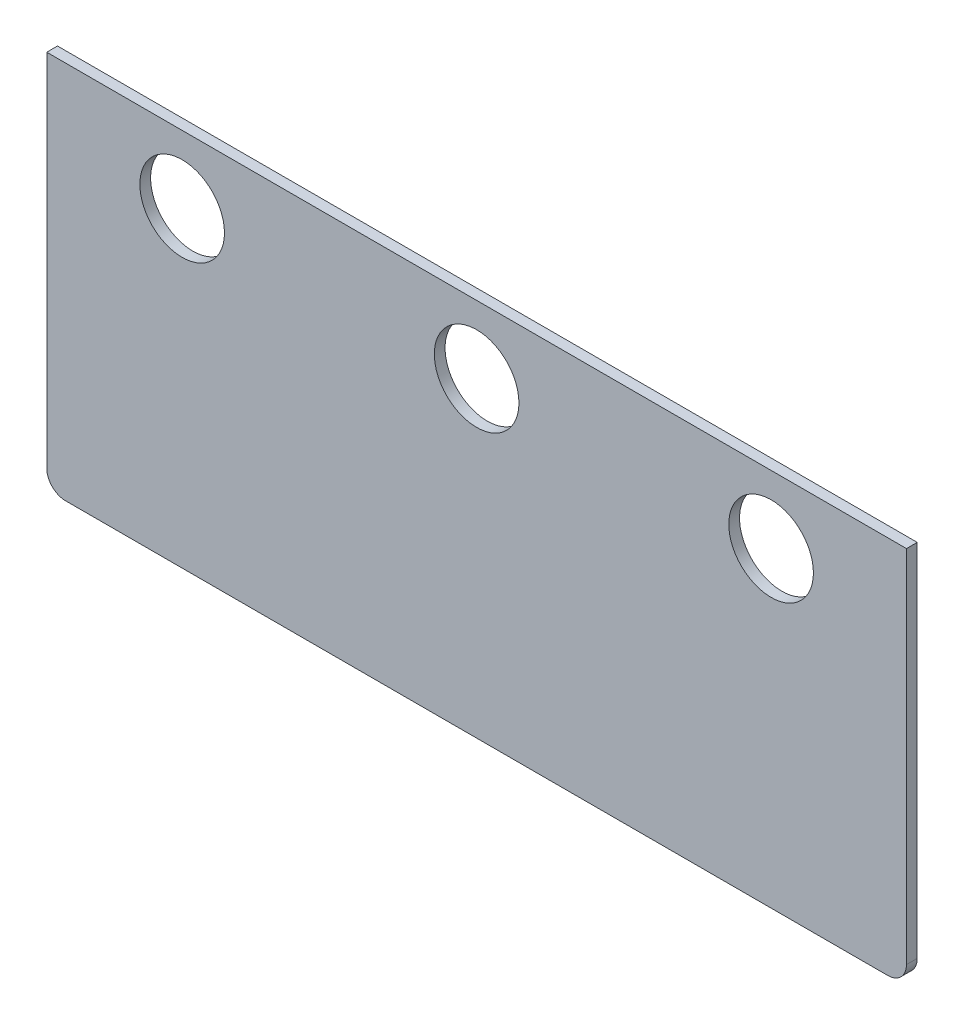
SolidWorks part; units mm, degrees
material "5052-H32"
ref_plane "Front Plane" through (0, 0, 0) normal (0, 0, 1) x (1, 0, 0)
ref_plane "Top Plane" through (0, 0, 0) normal (0, 1, 0) x (1, 0, 0)
ref_plane "Right Plane" through (0, 0, 0) normal (1, 0, 0) x (0, 0, -1)
sketch "Sketch1" plane through (0, 0, 0) normal (0, 0, 1) x (1, 0, 0)
  line L0 (-127, 112) -> (-127, 0)
  line L2 (127, 0) -> (127, 112)
  line L3 (127, 112) -> (-127, 112)
  line L4 (-127, 0) -> (127, 0)
  circle A0 centre (87, 92) radius 12.5
  circle A1 centre (0, 92) radius 12.5
  circle A2 centre (-87, 92) radius 12.5
  point P11 (0, 112)
  point P22 (0, 0)
  dimension "D4" = 25
  dimension "D1" = 112
  dimension "D2" = 254
  dimension "D3" = 20
  dimension "D5" = 40
  dimension "D6" = 40
extrude "Boss-Extrude1" add sketch "Sketch1" along normal blind 3.175
fillet "Fillet1" radius 5.5562 2 edges at (127, 0, 1.5875) (-127, 0, 1.5875)
equation "\"L\"= 420mm"
equation "\"W\"= 255mm"
equation "\"H\"= 110mm"
equation "\"Compartment Width\"= 80"
equation "\"T\"= 4.7625 * 2 / 3mm"
equation "\"Inside Fillet Radius\"= 5.55625mm"
equation "\"D1@Boss-Extrude1\"=\"T\""
equation "\"Hole\"=25mm"
equation "\"D4@Sketch1\"=\"Hole\""
equation "\"D2@Sketch1\"=\"W\"-1"
equation "\"D1@Sketch1\"=\"H\"+\"T\"-1.175"
equation "\"D1@Fillet1\"=\"Inside Fillet Radius\""
